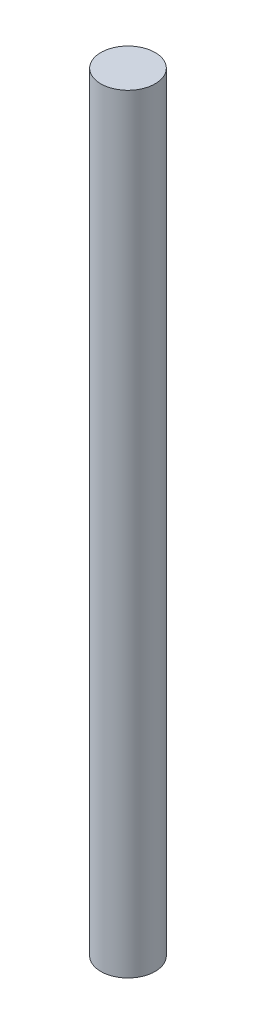
SolidWorks part; units mm, degrees
ref_plane "Front Plane" through (0, 0, 0) normal (0, 0, 1) x (1, 0, 0)
ref_plane "Top Plane" through (0, 0, 0) normal (0, 1, 0) x (1, 0, 0)
ref_plane "Right Plane" through (0, 0, 0) normal (1, 0, 0) x (0, 0, -1)
sketch "Sketch1" plane through (0, 0, 0) normal (0, 1, 0) x (1, 0, 0)
  circle A0 centre (0, 0) radius 6
  dimension "D1" = 12
extrude "Boss-Extrude1" add sketch "Sketch1" along normal blind 170
